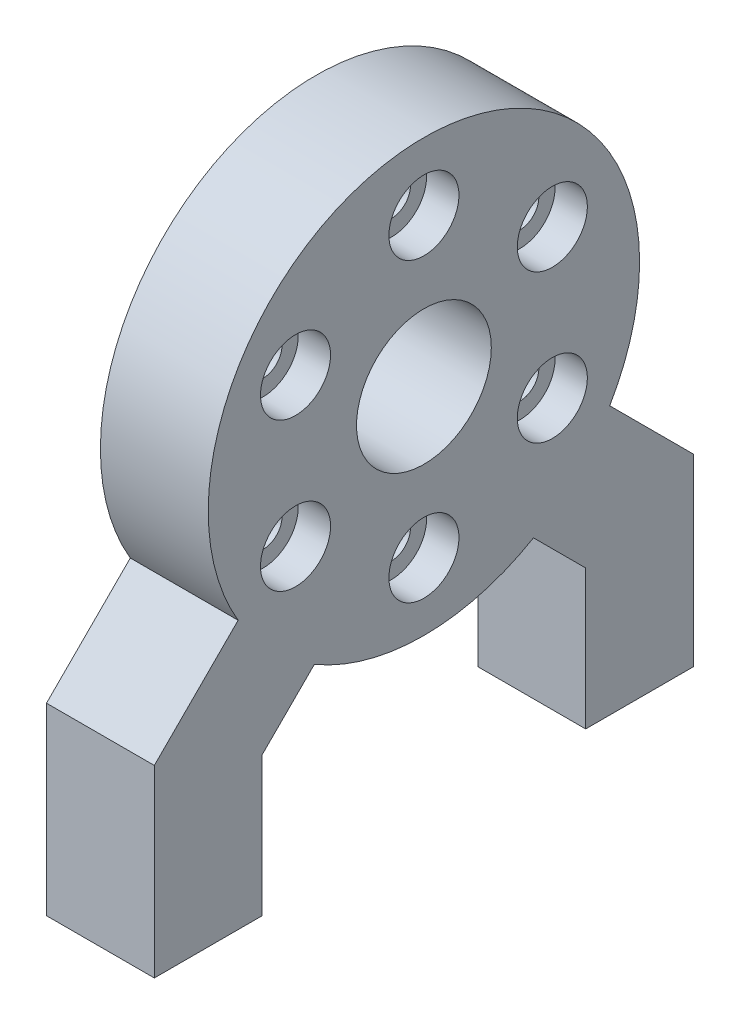
SolidWorks part; units mm, degrees
material "ABS"
ref_plane "Alzado" through (0, 0, 0) normal (0, 0, 1) x (1, 0, 0)
ref_plane "Planta" through (0, 0, 0) normal (0, 1, 0) x (1, 0, 0)
ref_plane "Vista lateral" through (0, 0, 0) normal (1, 0, 0) x (0, 0, -1)
sketch "Croquis1" plane through (0, 0, 0) normal (1, 0, 0) x (0, 0, -1)
  circle A0 centre (0, 0) radius 6.25
  circle A1 centre (0, 0) radius 13.75 construction
  circle A2 centre (0, 0) radius 20
  circle A3 centre (0, 13.75) radius 1.75
  circle A4 centre (11.9078, 6.875) radius 1.75
  circle A5 centre (11.9078, -6.875) radius 1.75
  circle A6 centre (0, -13.75) radius 1.75
  circle A7 centre (-11.9078, -6.875) radius 1.75
  circle A8 centre (-11.9078, 6.875) radius 1.75
  point P19 (0, 0)
  dimension "D1" = 12.5
  dimension "D2" = 27.5
  dimension "D3" = 40
  dimension "D4" = 3.5
  dimension "D5" = 6
extrude "Saliente-Extruir1" add sketch "Croquis1" along normal mid plane 10
sketch "Croquis2" plane through (0, 0, 0) normal (1, 0, 0) x (0, 0, -1)
  line L0 (0, 0) -> (0, -6.25) construction
  line L1 (0, 0) -> (-20, -20) construction
  line L2 (-20, -20) -> (-20, -35) construction
  line L3 (-15, -35) -> (-25, -35)
  line L4 (-25, -35) -> (-25, -17.9289)
  line L5 (-25, -17.9289) -> (-17.2286, -10.1575)
  line L6 (-15, -35) -> (-15, -22.0711)
  line L7 (-15, -22.0711) -> (-10.1575, -17.2286)
  line L8 (0, 5.5) -> (0, -5.5) construction
  line L9 (15, -35) -> (15, -22.0711)
  line L10 (15, -35) -> (25, -35)
  line L11 (25, -35) -> (25, -17.9289)
  line L12 (25, -17.9289) -> (17.2286, -10.1575)
  line L13 (15, -22.0711) -> (10.1575, -17.2286)
  circle A0 centre (0, 0) radius 6.25 construction
  circle A1 centre (0, 0) radius 20 construction
  arc A2 (-17.2286, -10.1575) -> (-10.1575, -17.2286) centre (0, 0) ccw
  arc A3 (17.2286, -10.1575) -> (10.1575, -17.2286) centre (0, 0) cw
  point P11 (-20, -35)
  dimension "D1" = 45
  dimension "D2" = 20
  dimension "D3" = 10
  dimension "D4" = 10
  dimension "D5" = 5
  dimension "D6" = 35
extrude "Saliente-Extruir2" add sketch "Croquis2" along normal mid plane 10
sketch "Croquis3" plane through (5, 0, 0) normal (1, 0, 0) x (0, 0, -1)
  circle A0 centre (0, 13.75) radius 3.25
  circle A1 centre (11.9078, 6.875) radius 3.25
  circle A2 centre (11.9078, -6.875) radius 3.25
  circle A3 centre (0, -13.75) radius 3.25
  circle A4 centre (-11.9078, -6.875) radius 3.25
  circle A5 centre (-11.9078, 6.875) radius 3.25
  point P15 (0, 0)
  dimension "D1" = 6.5
  dimension "D2" = 6
extrude "Cortar-Extruir1" cut sketch "Croquis3" against normal blind 3
sketch "Croquis4" plane through (0, -35, 0) normal (0, -1, 0) x (1, 0, 0)
  line L0 (0, 25) -> (0, 15) construction
  line L1 (5, 25) -> (-5, 25) construction
  line L2 (5, 15) -> (-5, 15) construction
  line L3 (0, 15) -> (0, -15) construction
  line L4 (5, -15) -> (-5, -15) construction
  line L5 (0, -15) -> (0, -25) construction
  line L6 (5, -25) -> (-5, -25) construction
  circle A0 centre (0, 20) radius 2.5
  circle A1 centre (0, -20) radius 2.5
  dimension "D1" = 5
extrude "Cortar-Extruir2" cut sketch "Croquis4" against normal blind 10
